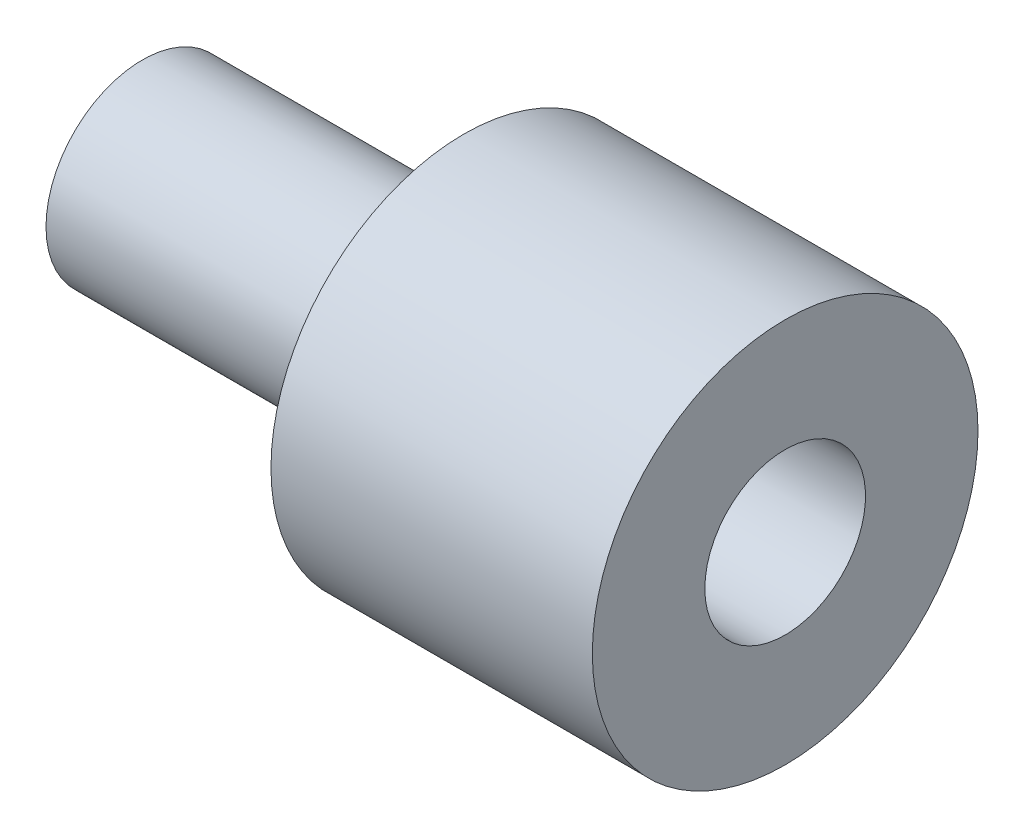
SolidWorks part; units mm, degrees
material "Oak"
ref_plane "Front" through (0, 0, 0) normal (0, 0, 1) x (1, 0, 0)
ref_plane "Top" through (0, 0, 0) normal (0, 1, 0) x (1, 0, 0)
ref_plane "Right" through (0, 0, 0) normal (1, 0, 0) x (0, 0, -1)
sketch "Sketch1" plane through (0, 0, 0) normal (0, 0, 1) x (1, 0, 0)
  line L7 (0, 0) -> (0, 5)
  line L8 (0, 5) -> (12, 5)
  line L9 (12, 5) -> (12, 12)
  line L10 (12, 12) -> (-8, 12)
  line L11 (-8, 12) -> (-8, 6)
  line L12 (-8, 6) -> (-28, 6)
  line L13 (-28, 6) -> (-28, 0)
  line L14 (-28, 0) -> (0, 0) construction
  line L15 (0, 0) -> (-28, 0)
  dimension "D1" = 12
  dimension "D2" = 10
  dimension "D3" = 24
  dimension "D4" = 12
  dimension "D5" = 40
  dimension "D6" = 20
revolve "Revolve1" add sketch "Sketch1" angle 360 about L14
